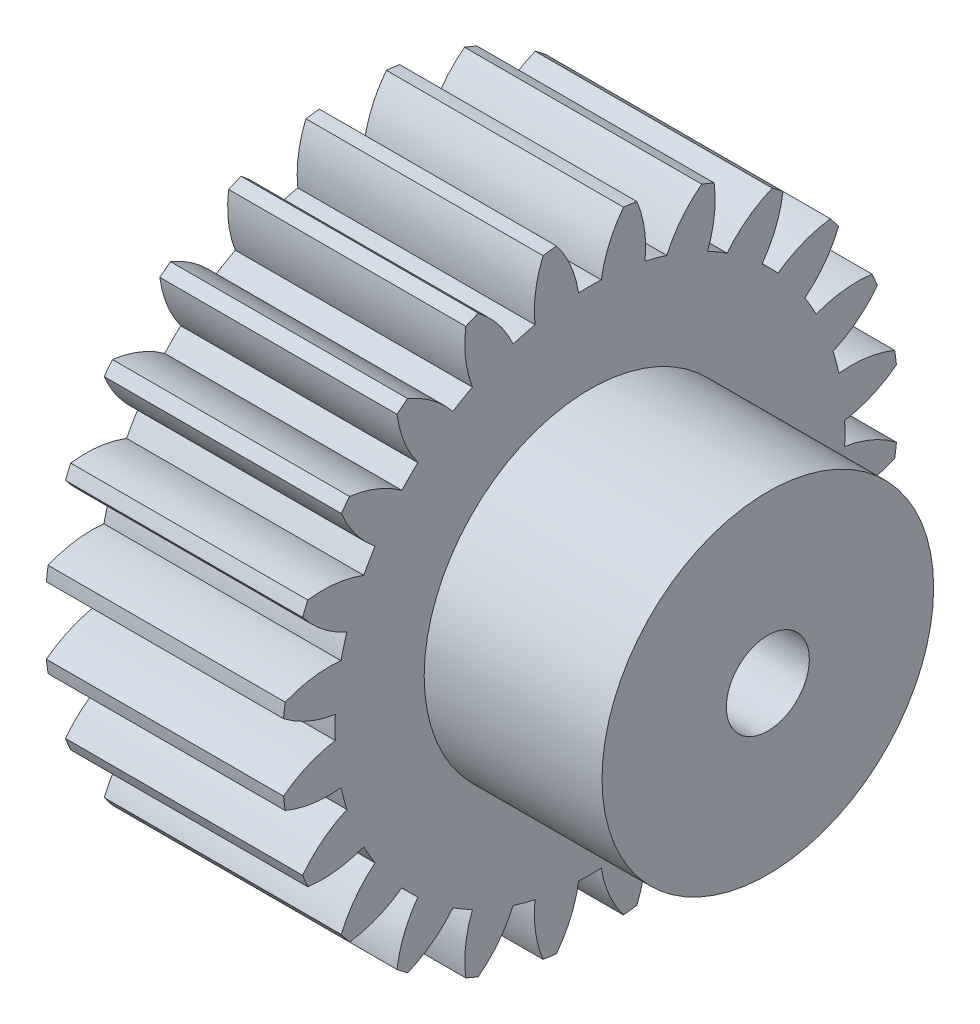
SolidWorks part; units mm, degrees
ref_plane "Plane1" through (0, 0, 0) normal (0, 0, 1) x (1, 0, 0)
ref_plane "Plane2" through (0, 0, 0) normal (0, 1, 0) x (1, 0, 0)
ref_plane "Plane3" through (0, 0, 0) normal (1, 0, 0) x (0, 0, -1)
sketch "HoldingSke" plane through (0, 0, 0) normal (0, 1, 0) x (1, 0, 0)
  line L0 (0, 0) -> (0.4568, -0.2034)
  line L1 (-15, 0) -> (100, 0) construction
  line L2 (0, 0) -> (-2.1039, 2.3779)
  line L3 (0, 0) -> (-11.863, 4.5341)
  line L4 (0, 0) -> (7.8894, 3.5126)
  line L5 (0, 0) -> (-46.8476, -17.4728)
  line L6 (0, 0) -> (-16.5793, -11.1861)
  line L7 (-2.1039, 2.3779) -> (8.6586, 51.2059)
  line L8 (-76.2, 54.61) -> (-75.2, 54.61)
  line L9 (-71.009, 38.7566) -> (-53.1078, 45.2721)
  line L10 (-76.2, 71.12) -> (104.1128, 71.12)
  line L11 (0, 0) -> (-20, 0)
  line L12 (-76.2, 101.6) -> (-76.133, 101.6)
  line L13 (24.9733, 27.94) -> (52.9518, 28.4284)
  line L14 (24.9733, 27.94) -> (24.9743, 27.94)
  line L15 (24.9733, 27.94) -> (100.4006, 29.5858)
  line L16 (-63.627, -2) -> (-12.827, -2)
  circle A0 centre (0, 0) radius 3.5
  circle A1 centre (0, 0) radius 21.499
  circle A2 centre (0, 0) radius 37.5
  circle A3 centre (0, 0) radius 3.5
  dimension "MHD" = 42.998
  dimension "Hub_dia" = 75
  dimension "Bore" = 7
  dimension "MBD" = 7
  dimension "Num_teeth" = 24
  dimension "Pitch" = 0.5
  dimension "Overall_len" = 50
  dimension "Show_teeth" = 24
  dimension "Thickness" = 20
  dimension "OAL" = 50.0001
  dimension "T_dim" = 1
  dimension "Ap" = 20
  dimension "H" = 19.05
  dimension "Pitch_radius" = 180.3128
  dimension "Width" = 20
  dimension "Backlash" = 0.067
  dimension "Addendum_fac" = 1
  dimension "Dedendum_fac" = 1.25
  dimension "Clearance_fac" = 0.25
  dimension "Dedendum_add" = 0.001
  dimension "Module" = 2
sketch "BasProSke" plane through (0, 0, 0) normal (0, 1, 0) x (1, 0, 0)
  line L0 (-10, 0) -> (60, 0) construction
  line L1 (0, 0) -> (0, 26)
  line L2 (0, 0) -> (20, 0)
  line L3 (20, 0) -> (20, 26)
  line L4 (20, 26) -> (0, 26)
  dimension "Thickness" = 20
  dimension "Diameter" = 52
revolve "Base-Revolve" add sketch "BasProSke" angle 360 about L0
sketch "TooCutSke" plane through (0, 0, 0) normal (1, 0, 0) x (0, 0, -1)
  line L1 (0, 0) -> (0, 107) construction
  line L2 (0, 0) -> (-1.6869, 23.9406) construction
  line L3 (0, 0) -> (-6.2538, 47.5021) construction
  line L4 (-1.6869, 23.9406) -> (-3.1269, 23.7511) construction
  arc A0 (0.9529, 21.4779) -> (-0.9529, 21.4779) centre (0, 0) ccw
  arc A1 (2.8465, 25.8693) -> (-2.8465, 25.8693) centre (0, 0) ccw
  circle A2 centre (0, 0) radius 24 construction
  circle A3 centre (0, 0) radius 22.5526 construction
  arc A4 (-0.9529, 21.4779) -> (-2.8465, 25.8693) centre (-10.4373, 19.9921) ccw
  arc A5 (2.8465, 25.8693) -> (0.9529, 21.4779) centre (10.4373, 19.9921) ccw
  dimension "Root_dia" = 42.998
  dimension "Overcut_dia" = 52.0508
  dimension "Pitch_dia" = 48
  dimension "Base_dia" = 45.1052
  dimension "Flank_rad" = 9.6
  dimension "Half_ang" = 7.5
  dimension "Half_CT" = 1.4524
extrude "ToothCut" cut sketch "TooCutSke" along normal through all
fillet "Breaks" [suppressed] radius 0.04
fillet "RootFillets" [suppressed] radius 0.501
pattern_circular "TeethCuts" count 24 every 15 about axis through (-10, 0, 0) along (1, 0, 0) of "ToothCut", "RootFillets", "Breaks"
sketch "HubNeaOneSke" plane through (0, 0, 0) normal (-1, 0, 0) x (0, 0, 1)
  circle A0 centre (0, 0) radius 21.499
  dimension "Diameter" = 42.998
extrude "HubNearOne" [suppressed] add sketch "HubNeaOneSke" along normal blind 30.0001
sketch "HubNeaBotSke" plane through (0, 0, 0) normal (-1, 0, 0) x (0, 0, 1)
  circle A0 centre (0, 0) radius 21.499
  dimension "Diameter" = 42.998
extrude "HubNearBoth" [suppressed] add sketch "HubNeaBotSke" along normal blind 15
ref_plane "FarPln" through (20, 0, 0) normal (1, 0, 0) x (0, 0, -1)
sketch "HubFarSke" plane through (20, 0, 0) normal (1, 0, 0) x (0, 0, -1)
  circle A0 centre (0, 0) radius 21.499
  dimension "Diameter" = 42.998
extrude "HubFar" [suppressed] add sketch "HubFarSke" along normal blind 15
sketch "BorSke" plane through (0, 0, 0) normal (1, 0, 0) x (0, 0, -1)
  circle A0 centre (0, 0) radius 3.5
  dimension "Diameter" = 7
extrude "Bore" cut sketch "BorSke" along normal mid plane 100.0001
sketch "KeySke" plane through (0, 0, 0) normal (1, 0, 0) x (0, 0, -1)
  line L0 (-1, 0) -> (-1, 4.5)
  line L1 (-1, 4.5) -> (1, 4.5)
  line L2 (1, 4.5) -> (1, 0)
  line L3 (0, 0) -> (0, 34) construction
  line L4 (-1, 0) -> (1, 0)
  dimension "Offset" = 4.5
extrude "Keyway" [suppressed] cut sketch "KeySke" along normal mid plane 100.0001
pattern_circular "Keyway2" [suppressed] count 2 every 90 about axis through (-10, 0, 0) along (1, 0, 0)
sketch "Esquisse1" plane through (20, 0, 0) normal (1, 0, 0) x (0, 0, -1)
  circle A0 centre (0, 0) radius 13.9829
  circle A1 centre (0, 0) radius 3.5
  dimension "D1" = 27.9658
sketch "Esquisse2" plane through (20, 0, 0) normal (1, 0, 0) x (0, 0, -1)
  circle A0 centre (0, 0) radius 13.9829
  circle A1 centre (0, 0) radius 3.5
extrude "Boss.-Extru.1" add sketch "Esquisse2" along normal blind 15
sketch "Esquisse3" plane through (0, 0, 0) normal (0, 1, 0) x (1, 0, 0)
  line L0 (35, -13.9829) -> (35, 13.9829) construction
  circle A0 centre (27.5, 1.2206) radius 2
  dimension "D2" = 4
  dimension "D1" = 7.5
extrude "Enlèv. mat.-Extru.1" cut sketch "Esquisse3" against normal blind 15
equation "' \"Module@HoldingSke\" = 6.35"
equation "' \"Num_teeth@HoldingSke\" = 12"
equation "' \"Ap@HoldingSke\" =  20"
equation "' \"Ap@HoldingSke\" = 20"
equation "' \"Width@HoldingSke\" = 0.5 * 25.4"
equation "' \"Hub_dia@HoldingSke\"= 1 * 25.4"
equation "' \"Hub_dia@HoldingSke\" = 1 * 25.4"
equation "' \"Overall_len@HoldingSke\" = 1.0 * 25.4"
equation "' \"Bore@HoldingSke\" = 0.75 * 25.4"
equation "' \"T_dim@HoldingSke\" = 0.1 * 25.4"
equation "' \"Width@KeySke\" = 0.25 * 25.4"
equation "' \"Show_teeth@HoldingSke\" = 13"
equation "' \"Backlash@HoldingSke\" = 0.009 * 25.4"
equation "' \"Addendum_fac@HoldingSke\" = 1.0"
equation "' \"Dedendum_fac@HoldingSke\" = 1.25"
equation "' \"Dedendum_add@HoldingSke\" = 0.00005 * 25.4"
equation "' \"Clearance_fac@HoldingSke\" = 0.25"
equation "\"Pitch@HoldingSke\" = 1 / \"Module@HoldingSke\""
equation "\"Overcut_dia@TooCutSke\" = (\"Num_teeth@HoldingSke\" + 2 * \"Addendum_fac@HoldingSke\") / \"Pitch@HoldingSke\" + 0.002 * 25.4"
equation "\"Pitch_dia@TooCutSke\" = \"Num_teeth@HoldingSke\" / \"Pitch@HoldingSke\""
equation "\"Base_dia@TooCutSke\" = \"Num_teeth@HoldingSke\" / \"Pitch@HoldingSke\" * cos((\"Ap@HoldingSke\"  * 3.14159265 / 180))"
equation "\"Root_dia@TooCutSke\" = (\"Num_teeth@HoldingSke\" + 2) / \"Pitch@HoldingSke\" - 2 * (\"Addendum_fac@HoldingSke\" + \"Dedendum_fac@HoldingSke\") / \"Pitch@HoldingSke\" - \"Dedendum_add@HoldingSke\" * 2"
equation "\"Half_ang@TooCutSke\" = 180 / \"Num_teeth@HoldingSke\""
equation "\"Half_CT@TooCutSke\" = \"Num_teeth@HoldingSke\" / \"Pitch@HoldingSke\" * sin((3.14159265 / 2 / \"Num_teeth@HoldingSke\")) / 2 - 7 * \"Backlash@HoldingSke\" / 4"
equation "\"Flank_rad@TooCutSke\" = \"Num_teeth@HoldingSke\" / \"Pitch@HoldingSke\" / 5"
equation "\"Radius@RootFillets\" = \"Clearance_fac@HoldingSke\" / \"Pitch@HoldingSke\" + \"Dedendum_add@HoldingSke\""
equation "\"Break_rad@Breaks\" = 0.02 / \"Pitch@HoldingSke\""
equation "\"Thickness@HoldingSke\" = \"Width@HoldingSke\""
equation "\"OAL@HoldingSke\" = \"Thickness@HoldingSke\""
equation "\"MHD@HoldingSke\" = (\"Num_teeth@HoldingSke\" + 2) / \"Pitch@HoldingSke\" - 2 * (\"Addendum_fac@HoldingSke\" + \"Dedendum_fac@HoldingSke\")  / \"Pitch@HoldingSke\" - \"Dedendum_add@HoldingSke\" * 2"
equation "\"MBD@HoldingSke\" = (\"Num_teeth@HoldingSke\" + 2) / \"Pitch@HoldingSke\" - 2 * (\"Addendum_fac@HoldingSke\" + \"Dedendum_fac@HoldingSke\")  / \"Pitch@HoldingSke\" - \"Dedendum_add@HoldingSke\" * 2 - 0.002 * 25.4"
equation "\"MHD@HoldingSke\" = ((sgn( \"MHD@HoldingSke\" - \"Hub_dia@HoldingSke\" )-1)*( \"MHD@HoldingSke\" - \"Hub_dia@HoldingSke\" ))/-2+ \"Hub_dia@HoldingSke\""
equation "\"MBD@HoldingSke\" = ((sgn( \"MBD@HoldingSke\" - \"Bore@HoldingSke\" )-1)*( \"MBD@HoldingSke\" - \"Bore@HoldingSke\" ))/-2+ \"Bore@HoldingSke\""
equation "\"OAL@HoldingSke\" = ((sgn( \"OAL@HoldingSke\" - \"Overall_len@HoldingSke\" )+1)*( \"OAL@HoldingSke\" - \"Overall_len@HoldingSke\" ))/2 + \"Overall_len@HoldingSke\" + 0.000002 * 25.4"
equation "\"Num_teeth@TeethCuts\" = int( \"Show_teeth@HoldingSke\" ) + 1"
equation "\"Num_teeth@TeethCuts\" = ((sgn( \"Num_teeth@TeethCuts\" - \"Num_teeth@HoldingSke\" )-1)*( \"Num_teeth@TeethCuts\" - \"Num_teeth@HoldingSke\" ))/-2+ \"Num_teeth@HoldingSke\""
equation "\"Num_teeth@TeethCuts\" = ((sgn( \"Num_teeth@TeethCuts\" - 2.0)+1)*( \"Num_teeth@TeethCuts\" - 2.0))/2 +2.0"
equation "\"Angle@TeethCuts\" = 360.0 / \"Num_teeth@HoldingSke\""
equation "\"Diameter@BasProSke\" = (\"Num_teeth@HoldingSke\" + 2 * \"Addendum_fac@HoldingSke\") / \"Pitch@HoldingSke\""
equation "\"Thickness@BasProSke\"  = \"Thickness@HoldingSke\""
equation "' \"Fillet_rad@BasProSke\" =  \"Thickness@HoldingSke\" * 0.05"
equation "' \"Fillet_rad@BasProSke\" = \"Thickness@HoldingSke\" * 0.05"
equation "\"MHD@HoldingSke\" = ((sgn( \"MHD@HoldingSke\" - \"Root_dia@TooCutSke\" )-1)*( \"MHD@HoldingSke\" - \"Root_dia@TooCutSke\" ))/-2+ \"Root_dia@TooCutSke\""
equation "\"Diameter@HubNeaOneSke\" = \"MHD@HoldingSke\""
equation "\"Length@HubNearOne\" = \"OAL@HoldingSke\" - \"Thickness@BasProSke\""
equation "\"Diameter@HubNeaBotSke\" = \"MHD@HoldingSke\""
equation "\"Length@HubNearBoth\" = ( \"OAL@HoldingSke\" - \"Thickness@BasProSke\" ) / 2.0"
equation "\"Thickness@FarPln\" = \"Thickness@BasProSke\""
equation "\"Diameter@HubFarSke\" = \"MHD@HoldingSke\""
equation "\"Length@HubFar\" = ( \"OAL@HoldingSke\" - \"Thickness@BasProSke\" ) / 2.0"
equation "\"Diameter@BorSke\" = \"MBD@HoldingSke\""
equation "\"D1@Bore\" = \"OAL@HoldingSke\" * 2.0"
equation "\"D1@Keyway\" = \"OAL@HoldingSke\" * 2.0"
equation "\"Offset@KeySke\" = \"T_dim@HoldingSke\" + \"MBD@HoldingSke\" / 2.0"
